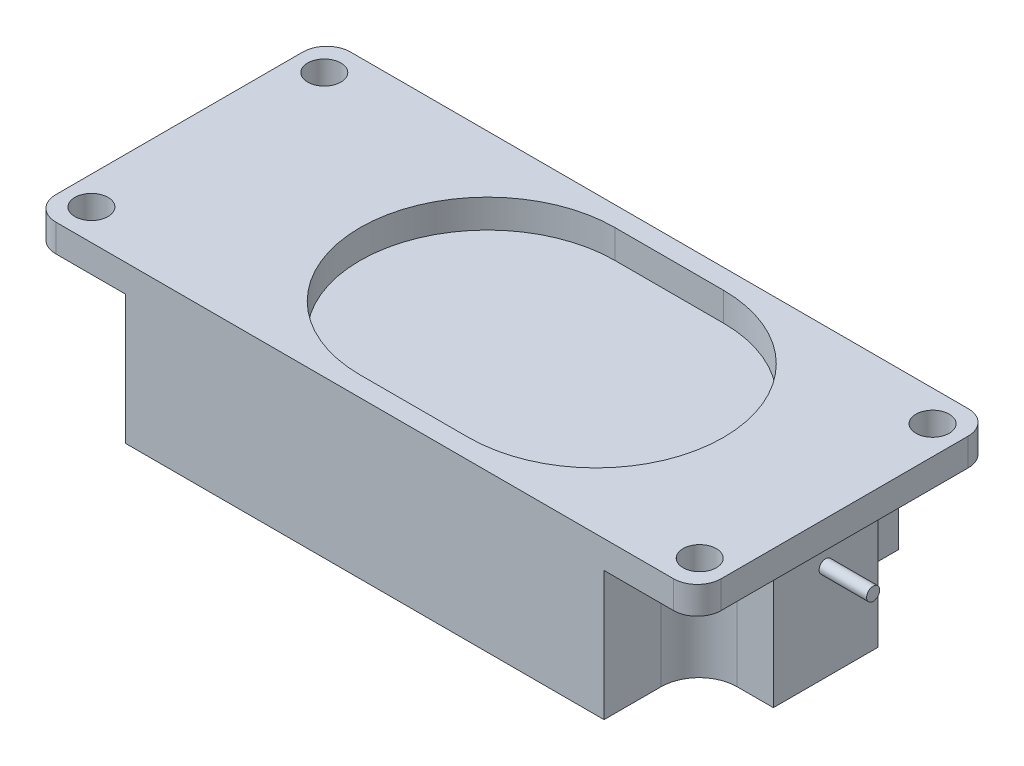
SolidWorks part; units mm, degrees
ref_plane "Front Plane" through (0, 0, 0) normal (0, 0, 1) x (1, 0, 0)
ref_plane "Top Plane" through (0, 0, 0) normal (0, 1, 0) x (1, 0, 0)
ref_plane "Right Plane" through (0, 0, 0) normal (1, 0, 0) x (0, 0, -1)
sketch "Sketch1" plane through (0, 0, 0) normal (0, 1, 0) x (1, 0, 0)
  line L0 (0, 0) -> (0, -9.0083) construction
  line L1 (35, 15.5) -> (-35, 15.5)
  line L2 (35, 15.5) -> (35, -15.5)
  line L3 (35, -15.5) -> (-35, -15.5)
  line L4 (-35, 15.5) -> (-35, -15.5)
  line L5 (35, 15.5) -> (-35, -15.5) construction
  line L6 (35, -15.5) -> (-35, 15.5) construction
  line L7 (0, 0) -> (-6.5004, 0) construction
  circle A0 centre (-32, 12.25) radius 1.75
  circle A1 centre (-32, -12.25) radius 1.75
  circle A2 centre (32, -12.25) radius 1.75
  circle A3 centre (32, 12.25) radius 1.75
  point P0 (0, 0)
  point P15 (0, 0)
  dimension "D3" = 3.5
  dimension "D4" = 64
  dimension "D5" = 24.5
  dimension "D1" = 70
  dimension "D2" = 31
extrude "Boss-Extrude1" add sketch "Sketch1" along normal blind 2.9
fillet "Fillet1" radius 2.5 4 edges at (-35, 1.45, -15.5) (35, 1.45, -15.5) (35, 1.45, 15.5) (-35, 1.45, 15.5)
sketch "Sketch2" plane through (0, 0, 0) normal (0, -1, 0) x (1, 0, 0)
  line L0 (-32.5, 15.5) -> (32.5, 15.5) construction
  line L1 (-25.185, -15.5) -> (25.185, -15.5)
  line L2 (-25.185, -15.5) -> (-25.185, -5.5)
  line L3 (-25.185, 15.5) -> (25.185, 15.5)
  line L4 (25.185, -15.5) -> (25.185, -5.5)
  line L5 (-25.185, -15.5) -> (25.185, 15.5) construction
  line L6 (-25.185, 15.5) -> (25.185, -15.5) construction
  line L7 (25.185, 5.5) -> (25.185, 15.5)
  line L8 (-33, -5.5) -> (-25.185, -5.5)
  line L9 (-33, -5.5) -> (-33, 5.5)
  line L10 (-33, 5.5) -> (-25.185, 5.5)
  line L11 (33, -5.5) -> (33, 5.5)
  line L12 (-33, -5.5) -> (33, 5.5) construction
  line L13 (-33, 5.5) -> (33, -5.5) construction
  line L14 (-25.185, 5.5) -> (-25.185, 15.5)
  line L15 (25.185, -5.5) -> (33, -5.5)
  line L16 (25.185, 5.5) -> (33, 5.5)
  point P0 (0, 0)
  point P8 (0, 0)
  dimension "D1" = 50.37
  dimension "D2" = 66
  dimension "D3" = 11
extrude "Boss-Extrude2" add sketch "Sketch2" along normal blind 13.6
fillet "Fillet2" radius 4 4 edges at (-25.185, -6.8, 5.5) (-25.185, -6.8, -5.5) (25.185, -6.8, -5.5) (25.185, -6.8, 5.5)
sketch "Sketch3" plane through (0, 2.9, 0) normal (0, 1, 0) x (1, 0, 0)
  line L0 (-2.575, 0) -> (8.835, 0) construction
  line L1 (-2.575, 13.415) -> (8.835, 13.415)
  line L2 (-2.575, -13.415) -> (8.835, -13.415)
  line L3 (35, -13) -> (35, 13) construction
  arc A0 (-2.575, 13.415) -> (-2.575, -13.415) centre (-2.575, 0) ccw
  arc A1 (8.835, -13.415) -> (8.835, 13.415) centre (8.835, 0) ccw
  point P3 (3.13, 0)
  point P10 (28.3349, 0)
  point P13 (14.8019, 0)
  dimension "D2" = 38.24
  dimension "D1" = 26.83
  dimension "D3" = 12.75
extrude "Cut-Extrude1" cut sketch "Sketch3" against normal blind 3
sketch "Sketch4" plane through (33, 0, 0) normal (1, 0, 0) x (0, 0, -1)
  circle A0 centre (0, -3.4643) radius 0.691
extrude "Boss-Extrude3" add sketch "Sketch4" along normal blind 5
